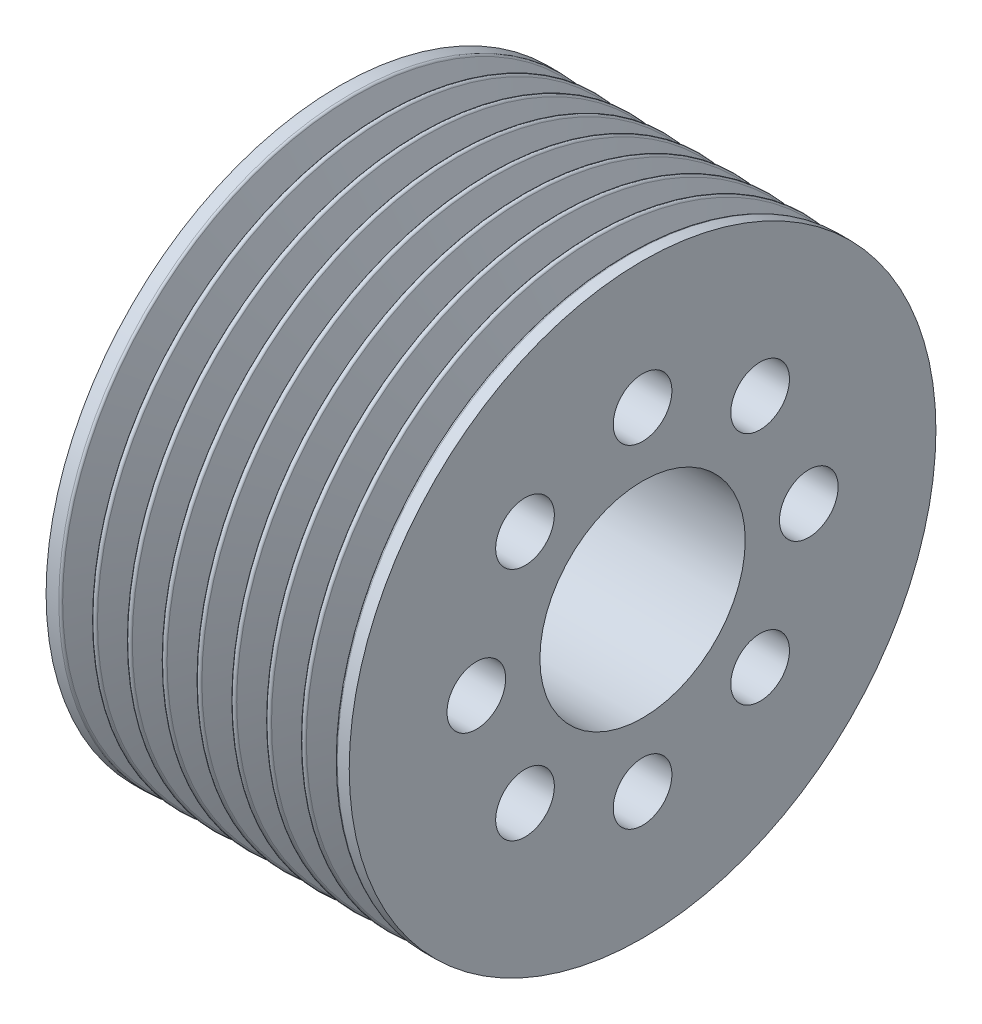
SolidWorks part; units mm, degrees
material "2018 Alloy"
ref_plane "Front Plane" through (0, 0, 0) normal (0, 0, 1) x (1, 0, 0)
ref_plane "Top Plane" through (0, 0, 0) normal (0, 1, 0) x (1, 0, 0)
ref_plane "Right Plane" through (0, 0, 0) normal (1, 0, 0) x (0, 0, -1)
sketch "Sketch1" plane through (0, 0, 0) normal (0, 0, 1) x (1, 0, 0)
  line L0 (49, 10.5) -> (49, 0) construction
  line L1 (49, 10.5) -> (49, 30)
  line L2 (49, 30) -> (18, 30)
  line L3 (18, 30) -> (18, 21.5)
  line L4 (49, 10.5) -> (31.5, 10.5)
  line L5 (0, 0) -> (49, 0) construction
  line L6 (18, 21.5) -> (31.5, 21.5)
  line L8 (0, 8.3175) -> (0, 0) construction
  line L9 (31.5, 10.5) -> (31.5, 21.5)
  dimension "D1" = 31
  dimension "D2" = 60
  dimension "D3" = 31.5
  dimension "D4" = 43
  dimension "D5" = 49
  dimension "D8" = 21
revolve "Revolve1" add sketch "Sketch1" angle 360 about L5
sketch "Sketch2" plane through (0, 0, 0) normal (0, 0, 1) x (1, 0, 0)
  line L0 (47.5458, 29.8376) -> (46.281, 26.4546)
  line L1 (45.719, 26.4546) -> (44.4542, 29.8376)
  line L2 (47.5458, 29.8376) -> (47.6066, 30) construction
  line L3 (49, 30) -> (18, 30) construction
  line L4 (44.4542, 29.8376) -> (44.3934, 30) construction
  line L5 (49, -30) -> (49, 30) construction
  line L6 (47.78, 30) -> (44.22, 30)
  line L7 (0, 0) -> (49, 0) construction
  arc A0 (47.5458, 29.8376) -> (47.78, 30) centre (47.78, 29.75) cw
  arc A1 (44.4542, 29.8376) -> (44.22, 30) centre (44.22, 29.75) ccw
  arc A2 (46.281, 26.4546) -> (45.719, 26.4546) centre (46, 26.5597) cw
  dimension "D2" = 0.25
  dimension "D3" = 0.3
  dimension "D1" = 41
  dimension "D4" = 3.56
  dimension "D5" = 3
revolve "Cut-Revolve1" cut sketch "Sketch2" angle 360 about L7
pattern_linear "LPattern1" count 8 spacing 3.56 along (-1, 0, 0) of "Cut-Revolve1"
sketch "Sketch3" plane through (49, 0, 0) normal (1, 0, 0) x (0, 0, -1)
  circle A0 centre (0, 0) radius 17 construction
  circle A1 centre (0, 17) radius 3
  circle A2 centre (12.0208, 12.0208) radius 3
  circle A3 centre (17, 0) radius 3
  circle A4 centre (12.0208, -12.0208) radius 3
  circle A5 centre (0, -17) radius 3
  circle A6 centre (-12.0208, -12.0208) radius 3
  circle A7 centre (-17, 0) radius 3
  circle A8 centre (-12.0208, 12.0208) radius 3
  dimension "D1" = 34
  dimension "D2" = 6
  dimension "D3" = 8
extrude "Cut-Extrude1" cut sketch "Sketch3" against normal up to surface (17.5 mm away) up to face at (31.5, 0, 10.5)
